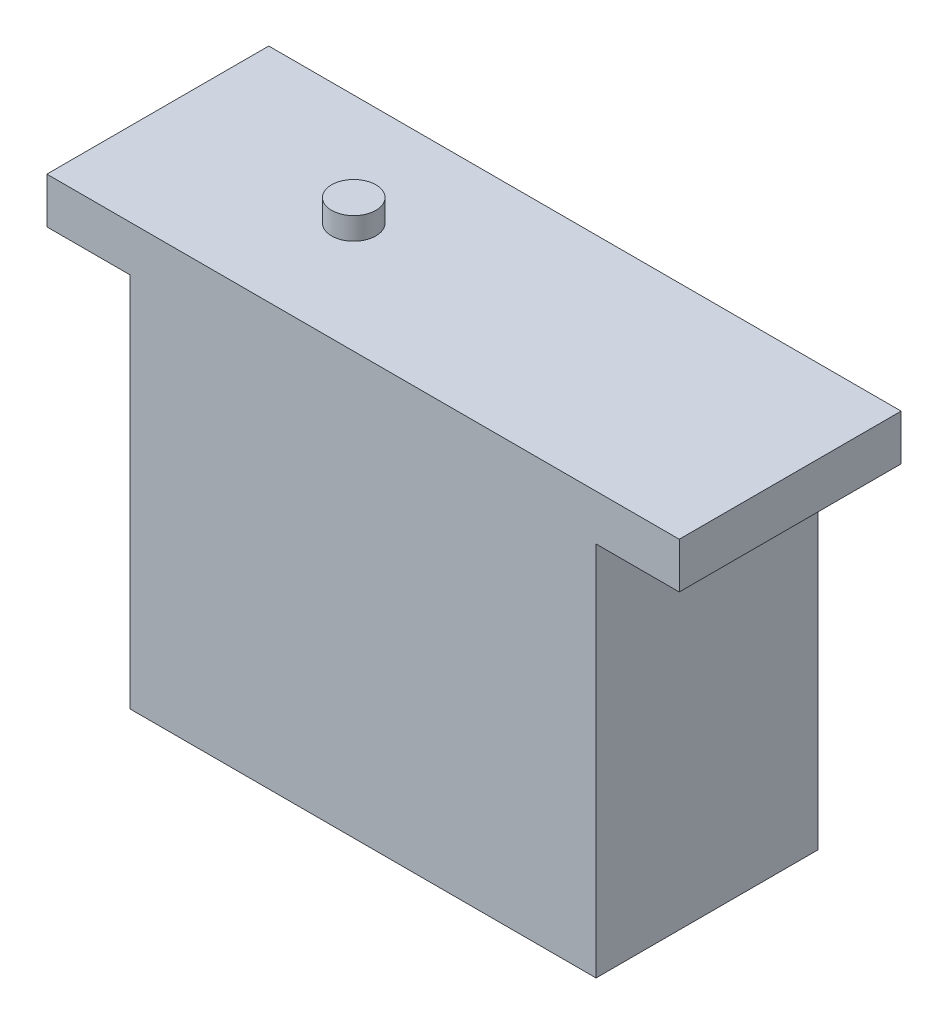
SolidWorks part; units mm, degrees
ref_plane "Front Plane" through (0, 0, 0) normal (0, 0, 1) x (1, 0, 0)
ref_plane "Top Plane" through (0, 0, 0) normal (0, 1, 0) x (1, 0, 0)
ref_plane "Right Plane" through (0, 0, 0) normal (1, 0, 0) x (0, 0, -1)
sketch "Sketch1" plane through (0, 0, 0) normal (0, 0, 1) x (1, 0, 0)
  line L1 (-21, -19) -> (21, -19)
  line L2 (-21, -19) -> (-21, 19)
  line L3 (-21, 19) -> (21, 19)
  line L4 (21, -19) -> (21, 19)
  line L5 (-21, -19) -> (21, 19) construction
  line L6 (-21, 19) -> (21, -19) construction
  point P0 (0, 0)
  dimension "D1" = 42
  dimension "D2" = 38
extrude "Boss-Extrude1" add sketch "Sketch1" along normal blind 20 contours L2 L1 L4 L3
sketch "Sketch3" plane through (0, 19, 0) normal (0, 1, 0) x (1, 0, 0)
  line L0 (-55, 0) -> (55, 0) construction
  line L1 (-21, -20) -> (-21, 0) construction
  circle A0 centre (-10.84, -10) radius 1.9959
  dimension "D1" = 10
  dimension "D2" = 10.16
extrude "Boss-Extrude2" add sketch "Sketch3" along normal blind 2
sketch "Sketch4" plane through (-21, 0, 0) normal (-1, 0, 0) x (0, 0, 1)
  line L0 (0, -22) -> (0, 22) construction
  line L1 (20, 19) -> (0, 19)
  line L2 (20, 19) -> (20, 14.8814)
  line L3 (20, 14.8814) -> (0, 14.8814)
  line L4 (0, 19) -> (0, 14.8814)
extrude "Boss-Extrude3" add sketch "Sketch4" along normal blind 7.5
mirror "Mirror2" about plane through (0, 0, 0) normal (1, 0, 0) of "Boss-Extrude3"
